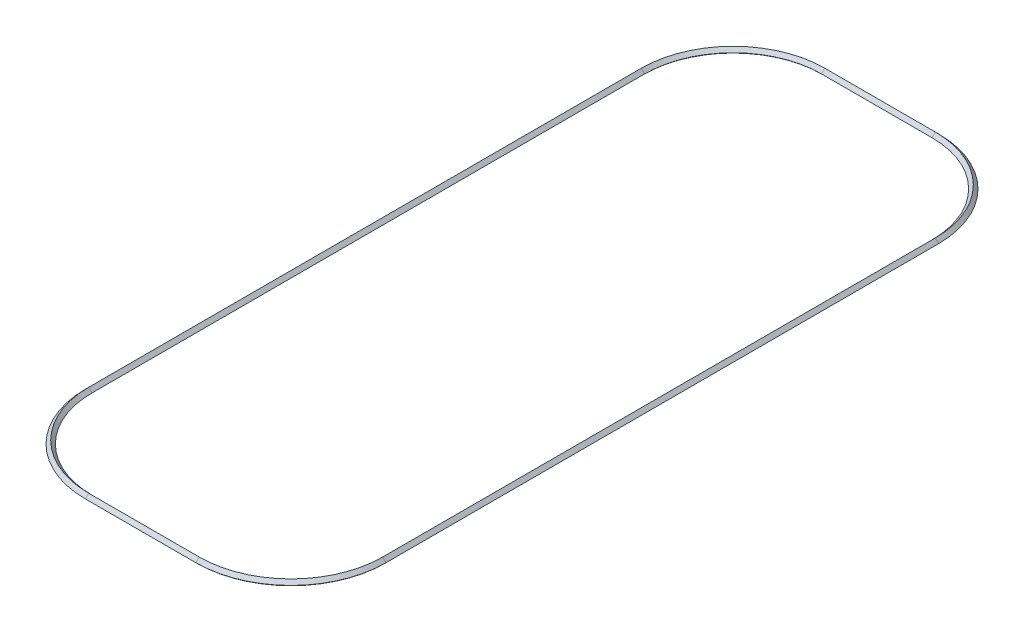
SolidWorks part; units mm, degrees
ref_plane "Plano frontal" through (0, 0, 0) normal (0, 0, 1) x (1, 0, 0)
ref_plane "Plano superior" through (0, 0, 0) normal (0, 1, 0) x (1, 0, 0)
ref_plane "Plano direito" through (0, 0, 0) normal (1, 0, 0) x (0, 0, -1)
sketch "Esboço1" plane through (0, 0, 0) normal (0, 0, 1) x (1, 0, 0)
  line L0 (0, 11.2289) -> (8.9803, 2.2486)
  line L1 (-8.9803, 2.2486) -> (-6.7317, 0)
  line L2 (0, 0) -> (0, 11.2289) construction
  line L3 (-6.7317, 0) -> (0, 6.7317)
  line L4 (8.9803, 2.2486) -> (6.7317, 0)
  line L5 (0, 11.2289) -> (-8.9803, 2.2486)
  line L6 (6.7317, 0) -> (0, 6.7317)
  dimension "D1" = 12.7
  dimension "D2" = 90
  dimension "D3" = 3.18
  dimension "D4" = 6.7317
sketch "Esboço2" plane through (0, 0, 0) normal (0, 1, 0) x (1, 0, 0)
  line L0 (0, -750) -> (0, 750)
  line L1 (0, 0) -> (-59.1058, 0) construction
  line L3 (249, 999) -> (549, 999)
  line L5 (798, 750) -> (798, -750)
  line L7 (549, -999) -> (249, -999)
  arc A0 (249, 999) -> (0, 750) centre (249, 750) ccw
  arc A1 (249, -999) -> (0, -750) centre (249, -750) cw
  arc A2 (798, 750) -> (549, 999) centre (549, 750) ccw
  arc A3 (549, -999) -> (798, -750) centre (549, -750) ccw
  point P10 (498, 0)
  dimension "D1" = 498
  dimension "D2" = 750
  dimension "D3" = 300
  dimension "D4" = 1998
sweep "Varredura1" add profiles "Esboço1" path "Esboço2"
